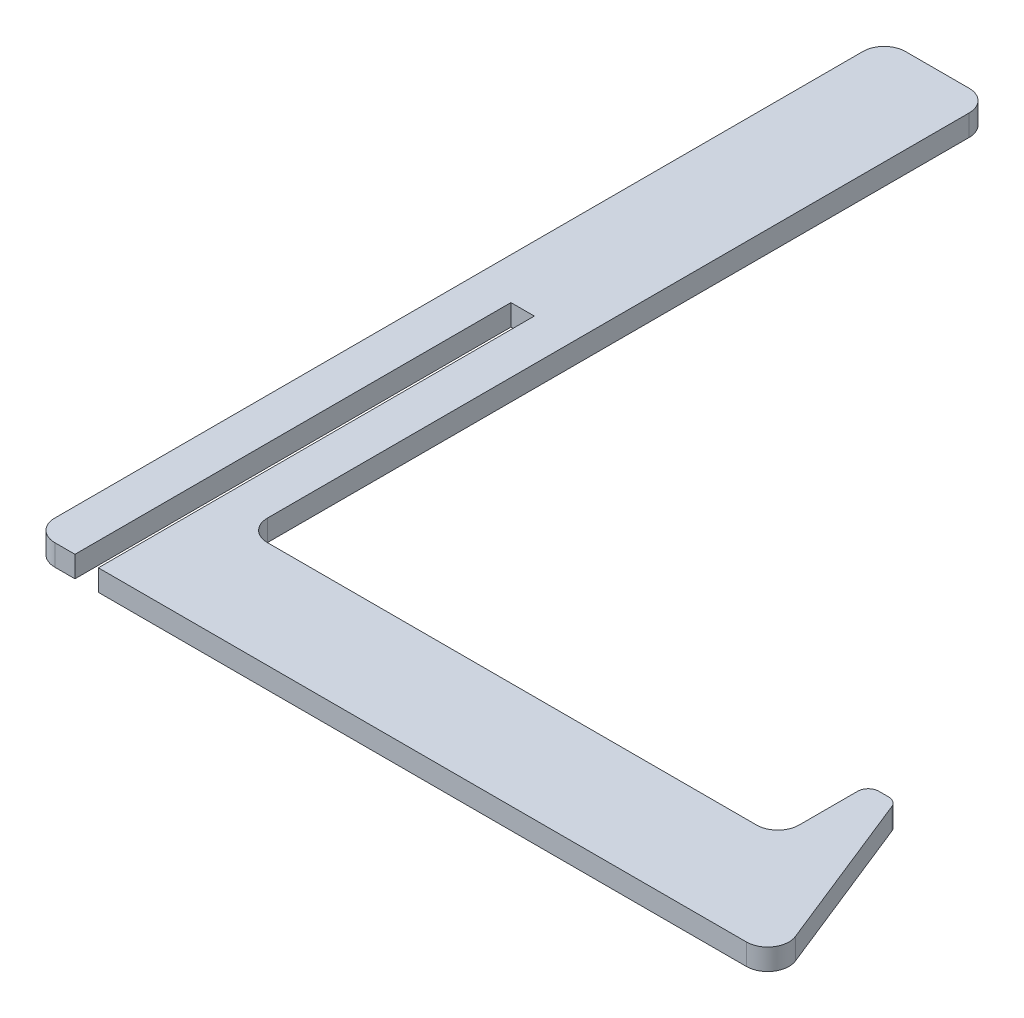
SolidWorks part; units mm, degrees
ref_plane "Front Plane" through (0, 0, 0) normal (0, 0, 1) x (1, 0, 0)
ref_plane "Top Plane" through (0, 0, 0) normal (0, 1, 0) x (1, 0, 0)
ref_plane "Right Plane" through (0, 0, 0) normal (1, 0, 0) x (0, 0, -1)
sketch "Sketch1" plane through (0, 0, 0) normal (0, 1, 0) x (1, 0, 0)
  line L0 (0, 0) -> (0, 80)
  line L1 (0, 80) -> (10, 80)
  line L2 (10, 80) -> (10, 10)
  line L3 (10, 10) -> (60, 10)
  line L4 (60, 10) -> (60, 25)
  line L5 (60, 25) -> (70, 0)
  line L6 (70, 0) -> (0, 0)
  dimension "D1" = 80
  dimension "D2" = 10
  dimension "D3" = 10
  dimension "D4" = 15
  dimension "D5" = 60
  dimension "D6" = 70
extrude "Boss-Extrude1" add sketch "Sketch1" along normal blind 2
fillet "Fillet1" radius 2 6 edges at (0, 1, 0) (70, 1, 0) (60, 1, -10) (10, 1, -10) (0, 1, -80) (10, 1, -80)
sketch "Sketch2" plane through (0, 2, 0) normal (0, 1, 0) x (1, 0, 0)
  line L0 (60, 18.5) -> (62.6, 18.5)
  line L1 (60, 25) -> (60, 12) construction
  line L2 (68.9029, 2.7428) -> (60, 25) construction
  line L3 (62.6, 18.5) -> (60, 25)
  line L4 (60, 25) -> (60, 18.5)
extrude "Cut-Extrude1" cut sketch "Sketch2" against normal through all
fillet "Fillet2" radius 1 2 edges at (62.6, 1, -18.5) (60, 1, -18.5)
sketch "Sketch3" plane through (0, 2, 0) normal (0, 1, 0) x (1, 0, 0)
  line L0 (2, 0) -> (67.0459, 0) construction
  line L1 (3.9, 0) -> (6.1, 0)
  line L2 (3.9, 0) -> (3.9, 41)
  line L3 (3.9, 41) -> (6.1, 41)
  line L4 (6.1, 0) -> (6.1, 41)
  line L5 (0, 78) -> (0, 2) construction
  line L6 (10, 12) -> (10, 78) construction
  line L7 (8, 80) -> (2, 80) construction
  dimension "D1" = 3.9
  dimension "D2" = 3.9
  dimension "D3" = 39
extrude "Cut-Extrude2" cut sketch "Sketch3" against normal through all
